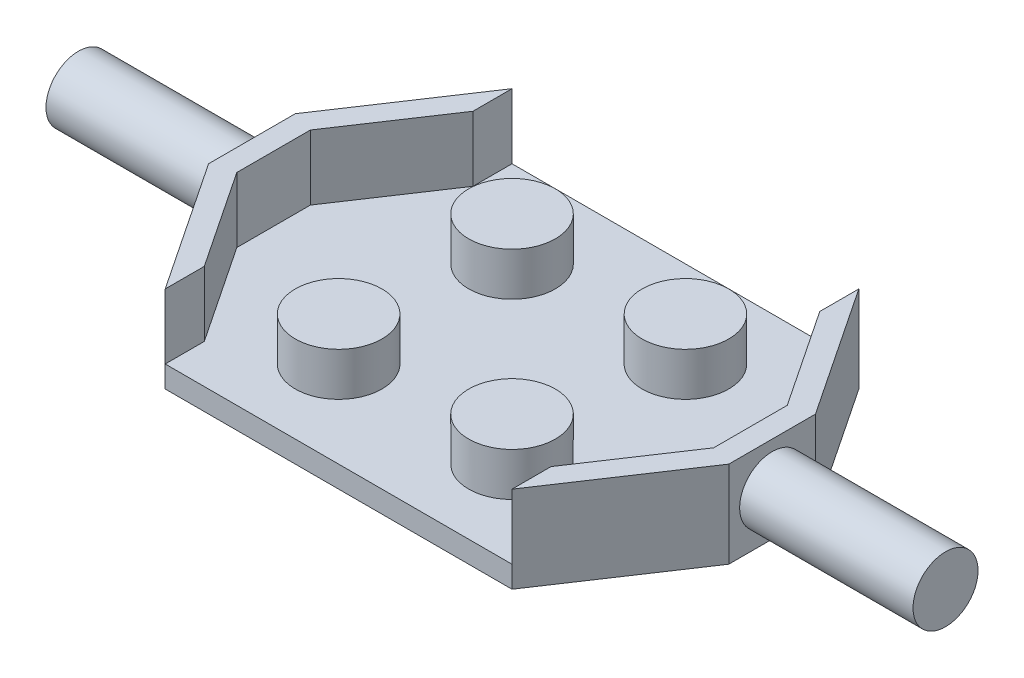
SolidWorks part; units mm, degrees
ref_plane "Front Plane" through (0, 0, 0) normal (0, 0, 1) x (1, 0, 0)
ref_plane "Top Plane" through (0, 0, 0) normal (0, 1, 0) x (1, 0, 0)
ref_plane "Right Plane" through (0, 0, 0) normal (1, 0, 0) x (0, 0, -1)
sketch "Sketch1" plane through (0, 0, 0) normal (0, 1, 0) x (1, 0, 0)
  line L0 (0, 0) -> (-12, 0)
  line L1 (-12, -2) -> (-12, 2)
  line L2 (-12, 2) -> (-8, 8)
  line L3 (-8, 8) -> (0, 8)
  line L4 (0, 8) -> (0, -8)
  line L5 (-8, -8) -> (0, -8)
  line L6 (-12, -2) -> (-8, -8)
  dimension "D1" = 12
  dimension "D2" = 8
  dimension "D3" = 8
  dimension "D4" = 2
extrude "Boss-Extrude1" add sketch "Sketch1" along normal blind 1 contours L1 L6 L5 L4 L0 | L4 L3 L2 L1 L0
sketch "Sketch2" plane through (0, 1, 0) normal (0, 1, 0) x (1, 0, 0)
  line L0 (0, 0) -> (-12, 0) construction
  line L1 (-12, -2) -> (-12, 2) construction
  line L2 (0, 8) -> (0, -8) construction
  line L3 (-8, 8) -> (0, 8) construction
  circle A0 centre (-4, 4) radius 2
  circle A1 centre (-4, -4) radius 2
  dimension "D1" = 4
  dimension "D2" = 4
  dimension "D3" = 4
extrude "Boss-Extrude2" add sketch "Sketch2" along normal blind 2
sketch "Sketch3" plane through (0, 1, 0) normal (0, 1, 0) x (1, 0, 0)
  line L0 (-12, -2) -> (-8, -8) construction
  line L1 (-12, -2) -> (-12, 2) construction
  line L2 (-12, 2) -> (-8, 8) construction
  line L3 (-12, -2) -> (-8, -8)
  line L4 (-12, -2) -> (-12, 2)
  line L5 (-12, 2) -> (-8, 8)
  line L6 (-11, -1.6972) -> (-8, -6.1972)
  line L7 (-11, -1.6972) -> (-11, 1.6972)
  line L8 (-11, 1.6972) -> (-8, 6.1972)
  line L9 (-8, 8) -> (-8, 6.1972)
  line L10 (-8, -6.1972) -> (-8, -8)
  line L11 (-11, 1.6972) -> (-7.1679, 7.4453) construction
  line L12 (-11, -1.6972) -> (-7.1679, -7.4453) construction
  dimension "D1" = 1
extrude "Boss-Extrude3" add sketch "Sketch3" along normal blind 3
sketch "Sketch4" plane through (-12, 0, 0) normal (-1, 0, 0) x (0, 0, 1)
  line L0 (0, 4) -> (0, 0) construction
  line L1 (-2, 4) -> (2, 4) construction
  circle A0 centre (0, 2) radius 1.5
  point P7 (0, 0)
  dimension "D1" = 3
extrude "Boss-Extrude4" add sketch "Sketch4" along normal blind 8
mirror "Mirror1" about plane through (0, 0, 0) normal (1, 0, 0) of "Boss-Extrude4", "Boss-Extrude3", "Boss-Extrude2", "Boss-Extrude1"
